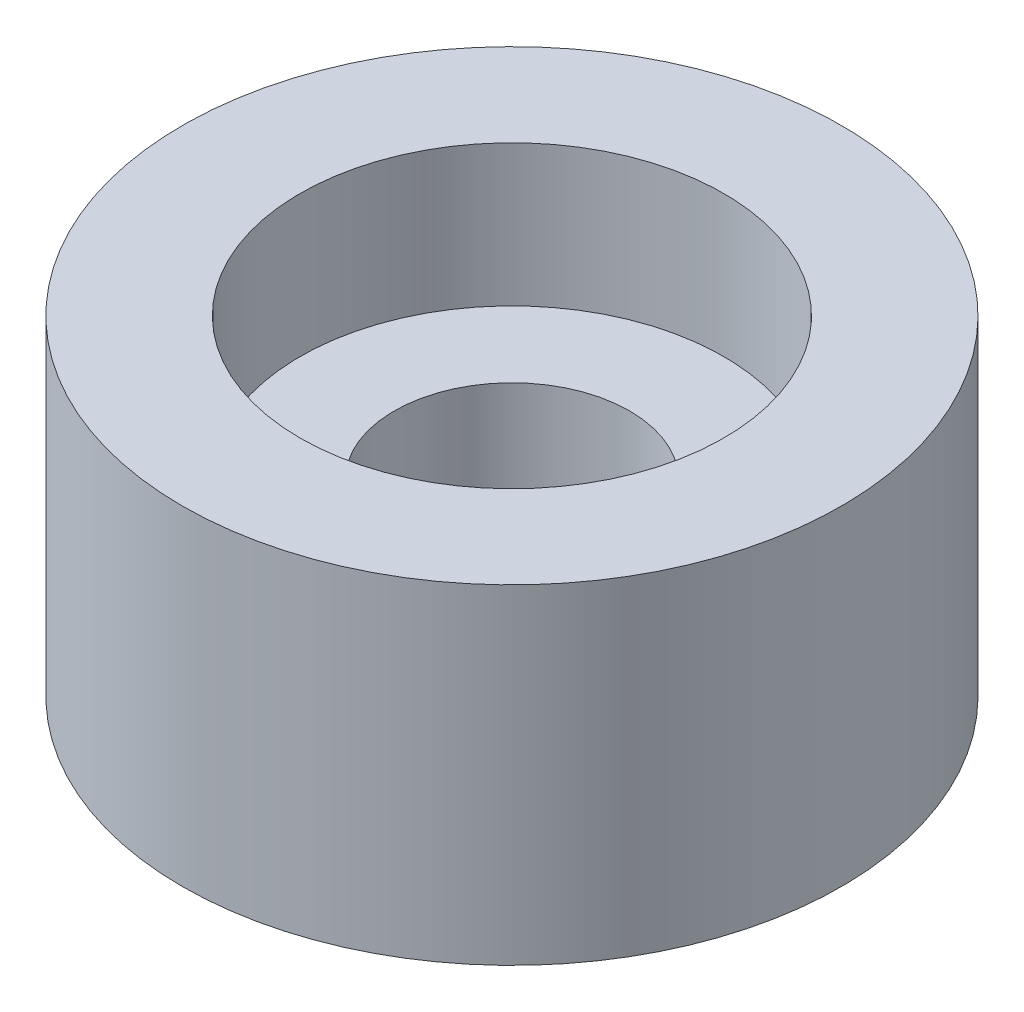
SolidWorks part; units mm, degrees
ref_plane "Front Plane" through (0, 0, 0) normal (0, 0, 1) x (1, 0, 0)
ref_plane "Top Plane" through (0, 0, 0) normal (0, 1, 0) x (1, 0, 0)
ref_plane "Right Plane" through (0, 0, 0) normal (1, 0, 0) x (0, 0, -1)
sketch "Sketch1" plane through (0, 0, 0) normal (0, 1, 0) x (1, 0, 0)
  circle A0 centre (0, 0) radius 3.5
  dimension "D1" = 7
extrude "Boss-Extrude1" add sketch "Sketch1" along normal blind 2 contours A0
sketch "Sketch2" plane through (0, 2, 0) normal (0, 1, 0) x (1, 0, 0)
  circle A0 centre (0, 0) radius 2.25
  circle A1 centre (0, 0) radius 3.5
  dimension "D1" = 4.5
  dimension "D2" = 7
extrude "Boss-Extrude2" add sketch "Sketch2" along normal blind 1.5
sketch "Sketch3" plane through (0, 0, 0) normal (0, -1, 0) x (1, 0, 0)
  circle A0 centre (0, 0) radius 2
  dimension "D1" = 4
extrude "Cut-Extrude1" cut sketch "Sketch3" against normal blind 1
sketch "Sketch4" plane through (0, 1, 0) normal (0, -1, 0) x (1, 0, 0)
  circle A0 centre (0, 0) radius 1.25
  dimension "D1" = 2.5
extrude "Cut-Extrude2" cut sketch "Sketch4" against normal blind 1
